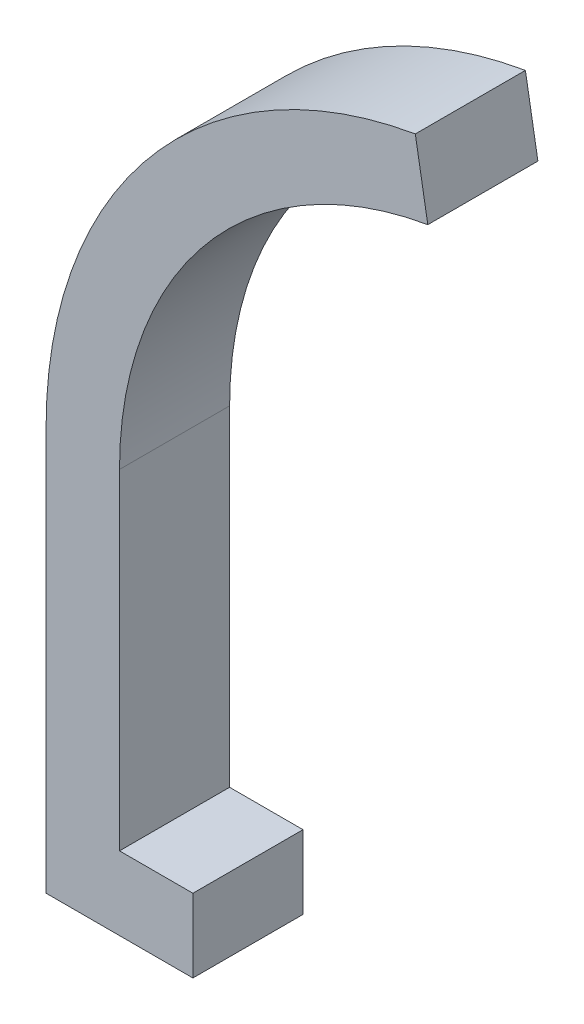
SolidWorks part; units mm, degrees
ref_plane "Ön Düzlem" through (0, 0, 0) normal (0, 0, 1) x (1, 0, 0)
ref_plane "Üst Düzlem" through (0, 0, 0) normal (0, 1, 0) x (1, 0, 0)
ref_plane "Sağ Düzlem" through (0, 0, 0) normal (1, 0, 0) x (0, 0, -1)
sketch "Sketch1" plane through (0, 0, 0) normal (0, 0, 1) x (1, 0, 0)
  line L0 (-110, 0) -> (0, 0) construction
  line L1 (0, 0) -> (0, 190) construction
  line L2 (-110, -20) -> (-90, -20)
  line L3 (-90, -20) -> (-90, -40)
  line L4 (-90, -40) -> (-130, -40)
  line L5 (-130, -40) -> (-130, 0)
  line L6 (-110, -20) -> (-110, 0)
  line L7 (-130, 0) -> (-130, 70)
  line L8 (-110, 0) -> (-110, 70)
  line L9 (-130, 0) -> (-110, 0) construction
  line L10 (-26, 169.7535) -> (-26, 190) construction
  line L12 (-26, 190) -> (0, 190) construction
  line L13 (-26, 169.7535) -> (-29.4043, 189.4617)
  arc A0 (-110, 70) -> (-26, 169.7535) centre (-8.7692, 70) cw
  arc A1 (-130, 70) -> (-29.4043, 189.4617) centre (-8.7692, 70) cw
  arc A2 (-29.4043, 189.4617) -> (-26, 190) centre (-8.7692, 70) cw construction
  dimension "D1" = 40
  dimension "D2" = 20
  dimension "D3" = 20
  dimension "D4" = 110
  dimension "D5" = 40
  dimension "D6" = 190
  dimension "D7" = 26
  dimension "D8" = 20
  dimension "D9" = 70
extrude "Boss-Extrude1" add sketch "Sketch1" along normal blind 30
